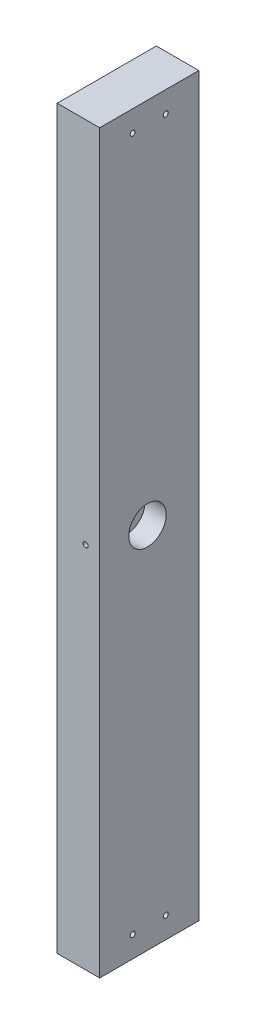
SolidWorks part; units mm, degrees
material "Pine"
ref_plane "Front Plane" through (0, 0, 0) normal (0, 0, 1) x (1, 0, 0)
ref_plane "Top Plane" through (0, 0, 0) normal (0, 1, 0) x (1, 0, 0)
ref_plane "Right Plane" through (0, 0, 0) normal (1, 0, 0) x (0, 0, -1)
sketch "Sketch1" plane through (0, 0, 0) normal (0, 1, 0) x (1, 0, 0)
  line L1 (0, 0) -> (38.1, 0)
  line L2 (0, 0) -> (0, 88.9)
  line L3 (0, 88.9) -> (38.1, 88.9)
  line L4 (38.1, 0) -> (38.1, 88.9)
  dimension "D1" = 38.1
  dimension "D2" = 88.9
extrude "Boss-Extrude1" add sketch "Sketch1" along normal blind 660.4
sketch "Sketch2" plane through (38.1, 0, 0) normal (1, 0, 0) x (0, 0, -1)
  line L0 (88.9, 330.2) -> (0, 330.2) construction
  line L1 (88.9, 660.4) -> (88.9, 0) construction
  line L2 (0, 660.4) -> (0, 0) construction
  circle A0 centre (42.8752, 330.2) radius 16.8275
  dimension "D1" = 33.655
  dimension "D2" = 42.8752
extrude "Cut-Extrude1" cut sketch "Sketch2" against normal blind 19.05
sketch "Sketch3" plane through (0, 0, 0) normal (0, 0, 1) x (1, 0, 0)
  line L0 (38.1, 330.2) -> (0, 330.2) construction
  line L1 (38.1, 660.4) -> (38.1, 0) construction
  line L2 (0, 660.4) -> (0, 0) construction
  circle A0 centre (25.4, 330.2) radius 2.2479
  dimension "D1" = 4.4958
  dimension "D2" = 12.7
extrude "Cut-Extrude2" cut sketch "Sketch3" against normal up to surface (26.0477 mm away)
sketch "Sketch4" plane through (38.1, 0, 0) normal (1, 0, 0) x (0, 0, -1)
  line L0 (88.9, 641.35) -> (0, 641.35) construction
  line L1 (88.9, 660.4) -> (88.9, 0) construction
  line L2 (0, 660.4) -> (0, 0) construction
  line L3 (0, 660.4) -> (88.9, 660.4) construction
  line L4 (88.9, 19.05) -> (0, 19.05) construction
  line L5 (0, 0) -> (88.9, 0) construction
  circle A0 centre (59.2667, 19.05) radius 2.2479
  circle A1 centre (29.6333, 19.05) radius 2.2479
  circle A2 centre (59.2667, 641.35) radius 2.2479
  circle A3 centre (29.6333, 641.35) radius 2.2479
  dimension "D3" = 4.4958
  dimension "D1" = 19.05
  dimension "D2" = 19.05
  dimension "D4" = 29.6333
  dimension "D5" = 29.6333
  dimension "D6" = 29.6333
  dimension "D7" = 29.6333
extrude "Cut-Extrude3" cut sketch "Sketch4" against normal through all
